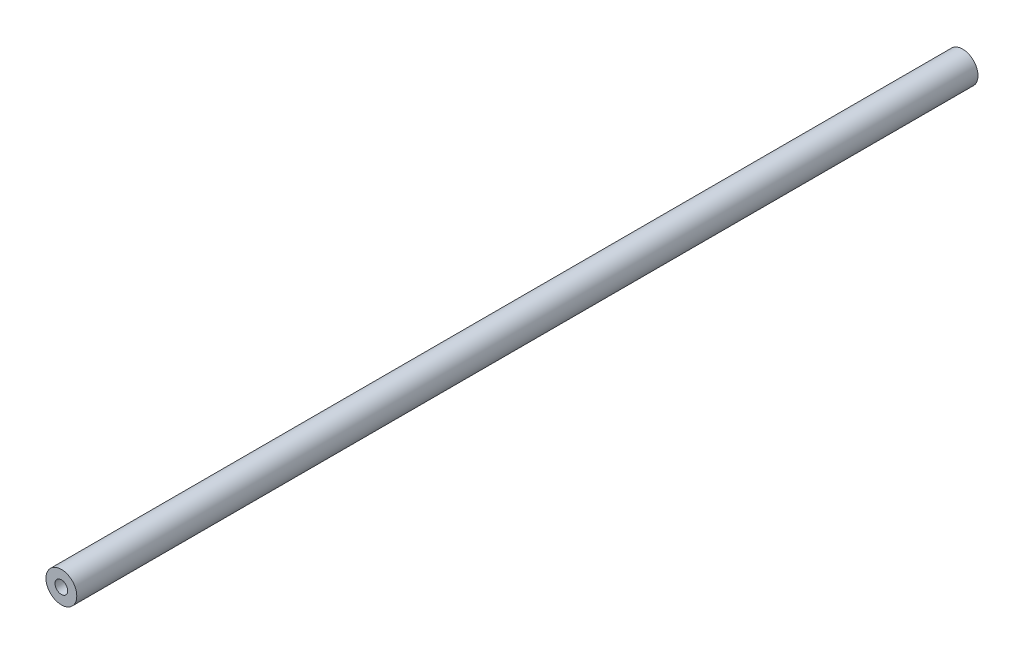
SolidWorks part; units mm, degrees
material "5052-H34"
ref_plane "正面" through (0, 0, 0) normal (0, 0, 1) x (1, 0, 0)
ref_plane "平面" through (0, 0, 0) normal (0, 1, 0) x (1, 0, 0)
ref_plane "右側面" through (0, 0, 0) normal (1, 0, 0) x (0, 0, -1)
sketch "ｽｹｯﾁ1" plane through (0, 0, 0) normal (0, 0, 1) x (1, 0, 0)
  circle A0 centre (0, 0) radius 4
  dimension "D1" = 8
extrude "ﾎﾞｽ - 押し出し1" add sketch "ｽｹｯﾁ1" along normal blind 234
sketch "ｽｹｯﾁ2" plane through (0, 0, 234) normal (0, 0, 1) x (1, 0, 0)
  circle A0 centre (0, 0) radius 1.65
  dimension "D1" = 3.3
extrude "ｶｯﾄ - 押し出し1" cut sketch "ｽｹｯﾁ2" against normal blind 15
sketch "ｽｹｯﾁ3" plane through (0, 0, 0) normal (0, 0, -1) x (-1, 0, 0)
  circle A0 centre (0, 0) radius 1.65
  dimension "D1" = 3.3
extrude "ｶｯﾄ - 押し出し2" cut sketch "ｽｹｯﾁ3" against normal blind 15
